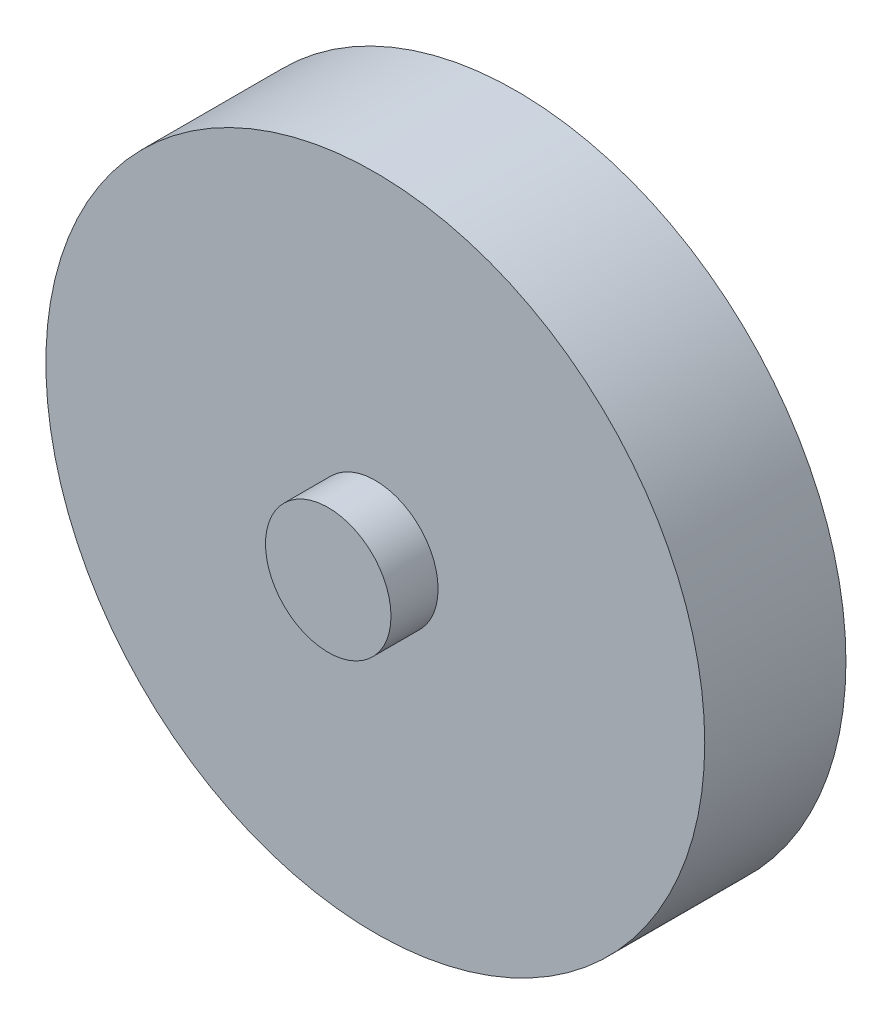
SolidWorks part; units mm, degrees
ref_plane "前视基准面" through (0, 0, 0) normal (0, 0, 1) x (1, 0, 0)
ref_plane "上视基准面" through (0, 0, 0) normal (0, 1, 0) x (1, 0, 0)
ref_plane "右视基准面" through (0, 0, 0) normal (1, 0, 0) x (0, 0, -1)
other "Configuration Table"
sketch "草图1" plane through (0, 0, 0) normal (0, 0, 1) x (1, 0, 0)
  circle A0 centre (0, 0) radius 8
extrude "凸台-拉伸1" add sketch "草图1" along normal blind 24
sketch "草图2" plane through (0, 0, 0) normal (0, 0, 1) x (1, 0, 0)
  circle A0 centre (0, 0) radius 42
extrude "凸台-拉伸2" add sketch "草图2" along normal blind 18
sketch "草图3" plane through (0, 0, 18) normal (0, 0, 1) x (1, 0, 0)
  line L0 (32.9516, 1.7869) -> (37.5326, 1.7869)
  line L1 (37.5326, 1.7869) -> (37.6055, 2.0362)
  line L2 (37.6055, 2.0362) -> (37.824, 2.0269)
  line L3 (37.824, 2.0269) -> (38.1865, 1.9892)
  line L4 (38.1865, 1.9892) -> (38.6899, 1.9052)
  line L5 (38.6899, 1.9052) -> (39.3292, 1.7573)
  line L6 (39.3292, 1.7573) -> (40.0978, 1.5285)
  line L7 (40.0978, 1.5285) -> (40.9876, 1.5285)
  line L8 (40.9876, 1.5285) -> (42, 0)
  line L9 (41.4938, 0.7643) -> (42, 1.5285)
  line L10 (42, 1.5285) -> (42, 3.2953)
  line L11 (42, 3.2953) -> (42, 4.5468)
  line L12 (42, 4.5468) -> (41.5984, 5.7942)
  line L13 (41.5984, 5.7942) -> (40.0978, 5.7942)
  line L14 (40.0978, 5.7942) -> (40.0978, 4.5468)
  line L15 (40.0978, 4.5468) -> (38.6899, 4.5468)
  line L16 (38.6899, 4.5468) -> (38.5116, 4.1707)
  line L17 (38.5116, 4.1707) -> (38.0276, 4.009)
  line L18 (38.0276, 4.009) -> (37.6754, 3.9151)
  line L19 (37.6754, 3.9151) -> (37.461, 3.8716)
  line L20 (37.461, 3.8716) -> (37.3889, 3.8612)
  line L21 (37.3889, 3.8612) -> (32.9516, 3.8612)
  line L22 (32.9516, 3.8612) -> (32.9516, 3.2953)
  line L23 (32.9516, 3.2953) -> (32.8983, 2.5891)
  line L24 (32.8983, 2.5891) -> (32.9516, 1.7869)
  circle A0 centre (0, 0) radius 42 construction
